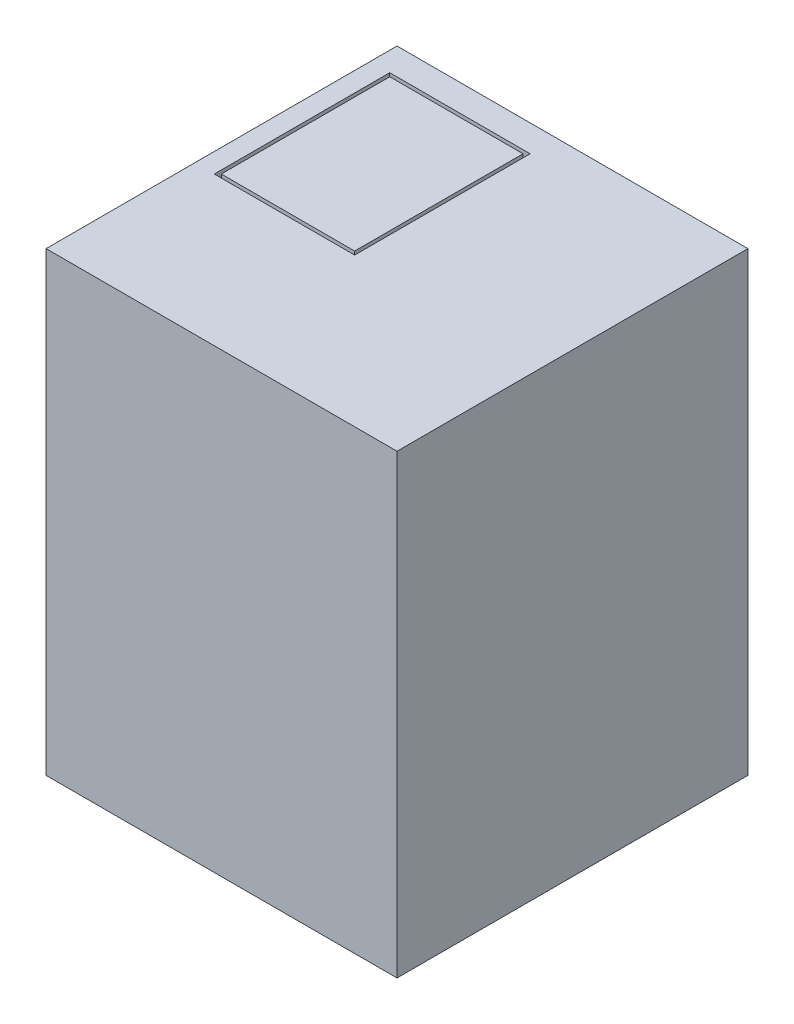
SolidWorks part; units mm, degrees
ref_plane "Front Plane" through (0, 0, 0) normal (0, 0, 1) x (1, 0, 0)
ref_plane "Top Plane" through (0, 0, 0) normal (0, 1, 0) x (1, 0, 0)
ref_plane "Right Plane" through (0, 0, 0) normal (1, 0, 0) x (0, 0, -1)
sketch "Sketch1" plane through (0, 0, 0) normal (0, 1, 0) x (1, 0, 0)
  line L1 (-50, 50) -> (50, 50)
  line L2 (-50, 50) -> (-50, -50)
  line L3 (-50, -50) -> (50, -50)
  line L4 (50, 50) -> (50, -50)
  line L5 (-50, 50) -> (50, -50) construction
  line L6 (-50, -50) -> (50, 50) construction
  point P0 (0, 0)
  dimension "D1" = 100
  dimension "D2" = 100
extrude "Boss-Extrude1" add sketch "Sketch1" along normal blind 130
sketch "Sketch2" plane through (0, 130, 0) normal (0, 1, 0) x (1, 0, 0)
  line L1 (-44.4396, 42.3703) -> (-4.4396, 42.3703)
  line L2 (-44.4396, 42.3703) -> (-44.4396, -7.6297)
  line L3 (-44.4396, -7.6297) -> (-4.4396, -7.6297)
  line L4 (-4.4396, 42.3703) -> (-4.4396, -7.6297)
  dimension "40" = 40
  dimension "52" = 50
extrude "Cut-Extrude1" cut sketch "Sketch2" against normal blind 5
sketch "Sketch3" plane through (0, 125, 0) normal (0, 1, 0) x (1, 0, 0)
  line L0 (-4.4396, -7.6297) -> (-4.4396, 42.3703) construction
  line L1 (-43.4396, 41.3703) -> (-5.4396, 41.3703)
  line L2 (-43.4396, 41.3703) -> (-43.4396, -6.6297)
  line L3 (-43.4396, -6.6297) -> (-5.4396, -6.6297)
  line L4 (-5.4396, 41.3703) -> (-5.4396, -6.6297)
  line L5 (-44.4396, -7.6297) -> (-4.4396, -7.6297) construction
  line L6 (-44.4396, 42.3703) -> (-44.4396, -7.6297) construction
  line L7 (-4.4396, 42.3703) -> (-44.4396, 42.3703) construction
  dimension "D1" = 1
  dimension "1" = 1
  dimension "D2" = 1
  dimension "D3" = 1
extrude "Boss-Extrude2" add sketch "Sketch3" along normal blind 5
